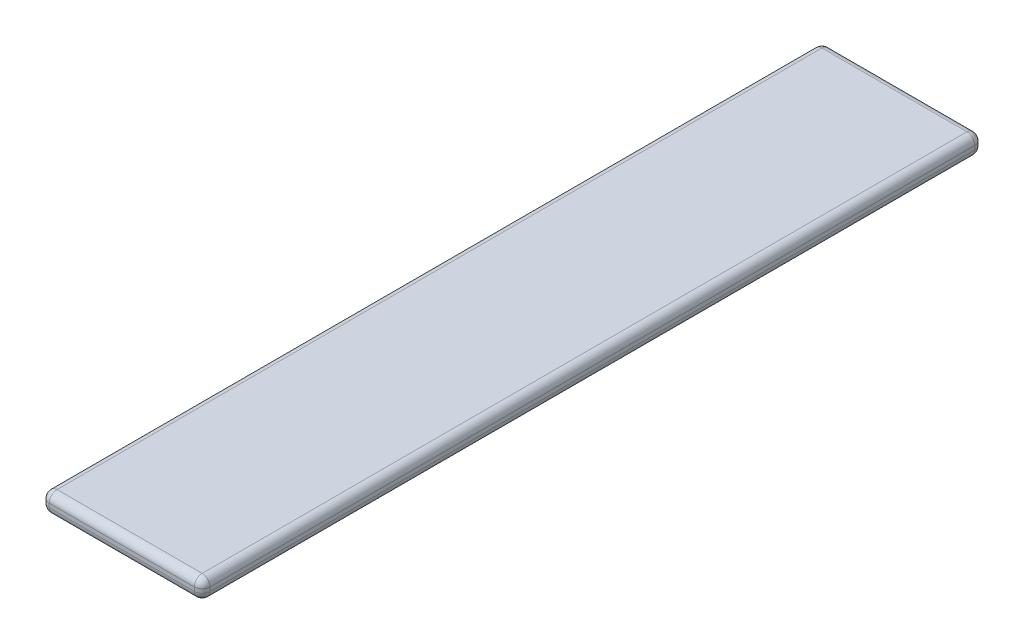
SolidWorks part; units mm, degrees
ref_plane "Front Plane" through (0, 0, 0) normal (0, 0, 1) x (1, 0, 0)
ref_plane "Top Plane" through (0, 0, 0) normal (0, 1, 0) x (1, 0, 0)
ref_plane "Right Plane" through (0, 0, 0) normal (1, 0, 0) x (0, 0, -1)
sketch "Sketch1" plane through (0, 0, 0) normal (0, 0, 1) x (1, 0, 0)
  line L1 (205, -25) -> (-205, -25)
  line L2 (205, -25) -> (205, 25)
  line L3 (205, 25) -> (-205, 25)
  line L4 (-205, -25) -> (-205, 25)
  line L5 (205, -25) -> (-205, 25) construction
  line L6 (205, 25) -> (-205, -25) construction
  point P0 (0, 0)
  dimension "D1" = 410
  dimension "D2" = 50
extrude "Boss-Extrude1" add sketch "Sketch1" along normal blind 1990
fillet "Fillet1" radius 20 12 edges at (-205, -25, 995) (205, -25, 995) (205, 25, 995) (-205, 25, 995) (0, 25, 1990) (205, 0, 1990) (0, -25, 1990) (-205, 0, 1990) (0, 25, 0) (205, 0, 0) (0, -25, 0) (-205, 0, 0)
